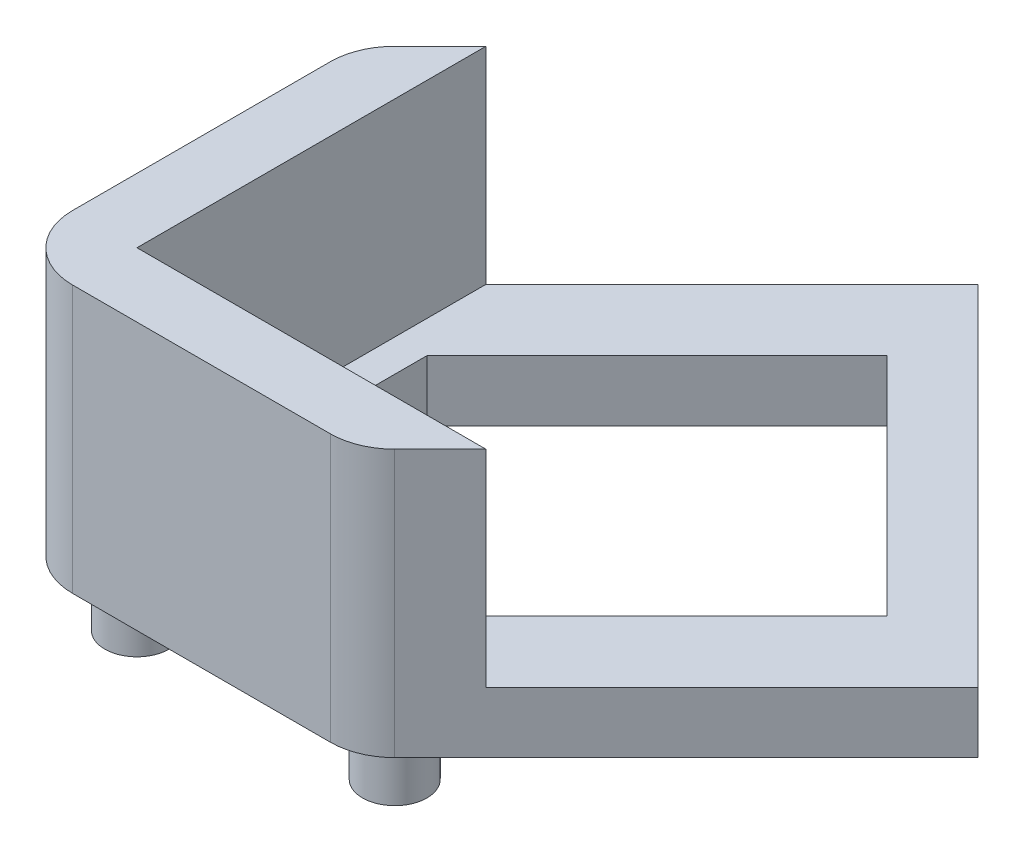
SolidWorks part; units mm, degrees
ref_plane "Front Plane" through (0, 0, 0) normal (0, 0, 1) x (1, 0, 0)
ref_plane "Top Plane" through (0, 0, 0) normal (0, 1, 0) x (1, 0, 0)
ref_plane "Right Plane" through (0, 0, 0) normal (1, 0, 0) x (0, 0, -1)
sketch "Sketch1" plane through (0, 0, 0) normal (0, 1, 0) x (1, 0, 0)
  line L0 (12.7, 0) -> (0, 0)
  line L1 (-1.5875, 0) -> (1.5875, 0)
  line L2 (-1.5875, 0) -> (-1.5875, 12.7)
  line L3 (-1.5875, 12.7) -> (1.5875, 12.7)
  line L4 (1.5875, 0) -> (1.5875, 12.7)
  line L5 (0, 1.5875) -> (12.7, 1.5875)
  line L6 (0, 1.5875) -> (0, -1.5875)
  line L7 (0, -1.5875) -> (12.7, -1.5875)
  line L8 (12.7, 1.5875) -> (12.7, -1.5875)
  line L9 (0, 0) -> (0, 15.875)
  line L10 (0, 15.875) -> (15.875, 0)
  line L11 (15.875, 0) -> (12.7, 0)
  line L12 (-3.175, 12.7) -> (-3.175, 0)
  line L13 (0, -3.175) -> (12.7, -3.175)
  circle A0 centre (0, 0) radius 1.5875
  circle A1 centre (0, 12.7) radius 1.5875
  circle A2 centre (12.7, 0) radius 1.5875
  circle A3 centre (0, 0) radius 3.175
  circle A4 centre (0, 12.7) radius 3.175
  circle A5 centre (12.7, 0) radius 3.175
  dimension "D1" = 3.175
  dimension "D2" = 12.7
  dimension "D3" = 12.7
sketch "Sketch2" plane through (0, 0, 0) normal (0, 1, 0) x (1, 0, 0)
  line L0 (0, -3.175) -> (12.7, -3.175) construction
  line L1 (-3.175, 12.7) -> (-3.175, 0) construction
  line L2 (0, -3.175) -> (12.7, -3.175)
  line L3 (-3.175, 12.7) -> (-3.175, 0)
  line L4 (16.6135, 24.8233) -> (24.8233, 16.6135)
  line L5 (22.5783, 14.3684) -> (14.3684, 22.5783)
  line L6 (-1.5875, 12.7) -> (1.5875, 12.7) construction
  line L12 (1.5875, 9.7974) -> (1.5875, 0)
  line L13 (1.5875, 0) -> (0, 1.5875)
  line L14 (0, 1.5875) -> (9.7974, 1.5875)
  line L15 (16.6135, 24.8233) -> (14.3684, 22.5783)
  line L21 (14.3684, 22.5783) -> (16.6135, 24.8233)
  line L22 (14.3684, 22.5783) -> (12.9171, 24.0296)
  line L23 (1.5875, 12.7) -> (12.9171, 24.0296)
  line L25 (16.6135, 24.8233) -> (12.1233, 29.3135)
  line L27 (12.1233, 29.3135) -> (-2.2451, 14.9451)
  line L28 (1.5875, 9.7974) -> (1.5875, 12.7)
  line L29 (9.7974, 1.5875) -> (12.7, 1.5875)
  line L30 (1.5875, 1.5875) -> (0, 0) construction
  line L31 (12.7, 1.5875) -> (24.0296, 12.9171)
  line L33 (29.3135, 12.1233) -> (14.9451, -2.2451)
  line L34 (24.8233, 16.6135) -> (29.3135, 12.1233)
  line L35 (24.8233, 16.6135) -> (22.5783, 14.3684)
  line L40 (22.5783, 14.3684) -> (24.0296, 12.9171)
  circle A1 centre (0, 0) radius 3.175
  arc A2 (-3.175, 0) -> (0, -3.175) centre (0, 0) ccw
  circle A11 centre (0, 12.7) radius 3.175
  arc A12 (-2.2451, 14.9451) -> (-3.175, 12.7) centre (0, 12.7) ccw
  arc A13 (12.7, -3.175) -> (14.9451, -2.2451) centre (12.7, 0) ccw
  dimension "D2" = 3.175
  dimension "D6" = 6.35
  dimension "D7" = 45
  dimension "D1" = 0
  dimension "D8" = 0
extrude "Boss-Extrude1" add sketch "Sketch2" along normal blind 3
sketch "Sketch5" plane through (0, 0, 0) normal (0, -1, 0) x (1, 0, 0)
  line L0 (0, -1.5875) -> (0, 1.5875) construction
  circle A0 centre (0, 0) radius 1.5875
  circle A1 centre (12.7, 0) radius 1.5875
  circle A2 centre (0, -12.7) radius 1.5875
extrude "Boss-Extrude4" add sketch "Sketch5" along normal blind 3.175
sketch "Sketch6" plane through (0, 3, 0) normal (0, 1, 0) x (1, 0, 0)
  line L0 (1.5875, 1.5875) -> (1.5875, 18.7776)
  line L1 (12.1233, 29.3135) -> (-2.2451, 14.9451) construction
  line L2 (1.5875, 1.5875) -> (18.7776, 1.5875)
  line L3 (29.3135, 12.1233) -> (14.9451, -2.2451) construction
  line L9 (0, -3.175) -> (12.7, -3.175)
  line L10 (14.9451, -2.2451) -> (29.3135, 12.1233)
  line L11 (29.3135, 12.1233) -> (12.1233, 29.3135)
  line L12 (12.1233, 29.3135) -> (-2.2451, 14.9451)
  line L13 (-3.175, 12.7) -> (-3.175, 0)
  line L14 (0, -3.175) -> (12.7, -3.175)
  line L15 (14.9451, -2.2451) -> (29.3135, 12.1233)
  line L16 (29.3135, 12.1233) -> (12.1233, 29.3135)
  line L17 (12.1233, 29.3135) -> (-2.2451, 14.9451)
  line L18 (-3.175, 12.7) -> (-3.175, 0)
  arc A3 (12.7, -3.175) -> (14.9451, -2.2451) centre (12.7, 0) ccw
  arc A4 (-2.2451, 14.9451) -> (-3.175, 12.7) centre (0, 12.7) ccw
  arc A5 (-3.175, 0) -> (0, -3.175) centre (0, 0) ccw
  arc A6 (12.7, -3.175) -> (14.9451, -2.2451) centre (12.7, 0) ccw
  arc A7 (-2.2451, 14.9451) -> (-3.175, 12.7) centre (0, 12.7) ccw
  arc A8 (-3.175, 0) -> (0, -3.175) centre (0, 0) ccw
  line M12 (12.7, 1.5875) -> (1.5875, 1.5875)
  line M13 (1.5875, 1.5875) -> (1.5875, 12.7)
  line M14 (0, -3.175) -> (12.7, -3.175)
  arc M15 (12.7, -3.175) -> (14.9451, -2.2451) centre (12.7, 0) ccw
  line M16 (14.9451, -2.2451) -> (29.3135, 12.1233)
  line M18 (12.1233, 29.3135) -> (-2.2451, 14.9451)
  arc M19 (-2.2451, 14.9451) -> (-3.175, 12.7) centre (0, 12.7) ccw
  line M20 (-3.175, 12.7) -> (-3.175, 0)
  arc M21 (-3.175, 0) -> (0, -3.175) centre (0, 0) ccw
  dimension "D1" = 0
extrude "Boss-Extrude5" add sketch "Sketch6" along normal blind 10.16 contours L2 L0 M12 M13 M18 M19 M20 M21 M14 M15 M16
sketch "Sketch7" plane through (0, 13.16, 0) normal (0, 1, 0) x (1, 0, 0)
  line L0 (0, -3.175) -> (12.7, -3.175) construction
  line L1 (-3.175, 12.7) -> (-3.175, 0) construction
  line L2 (0, -3.175) -> (12.7, -3.175)
  line L3 (-3.175, 12.7) -> (-3.175, 0)
  line L4 (12.7, 1.5875) -> (0, 1.5875)
  line L5 (12.7, -1.5875) -> (12.7, 1.5875)
  line L6 (0, -1.5875) -> (12.7, -1.5875)
  line L7 (0, 1.5875) -> (0, -1.5875)
  line L8 (12.7, 1.5875) -> (1.5875, 1.5875)
  line L9 (12.7, -1.5875) -> (12.7, 0)
  line L10 (0, -1.5875) -> (12.7, -1.5875)
  line L11 (0, 1.5875) -> (0, -1.5875)
  line L12 (-1.5875, 0) -> (1.5875, 0)
  line L13 (1.5875, 0) -> (1.5875, 12.7)
  line L14 (1.5875, 12.7) -> (-1.5875, 12.7)
  line L15 (-1.5875, 12.7) -> (-1.5875, 0)
  line L16 (-1.5875, 0) -> (1.5875, 0)
  line L18 (0, 12.7) -> (-1.5875, 12.7)
  line L19 (-1.5875, 12.7) -> (-1.5875, 0)
  line L20 (15.875, 0) -> (0, 15.875)
  line L21 (12.7, 0) -> (15.875, 0)
  line L22 (0, 0) -> (12.7, 0)
  line L23 (0, 15.875) -> (0, 0)
  line L25 (12.7, 0) -> (15.875, 0)
  line L26 (0, 0) -> (12.7, 0)
  line L27 (0, 15.875) -> (0, 0)
  line L28 (0, 15.875) -> (0, 17.1901)
  line L29 (1.5875, 18.7776) -> (-2.2451, 14.9451) construction
  line L30 (0, 17.1901) -> (1.5875, 18.7776)
  line L31 (1.5875, 18.7776) -> (18.7776, 1.5875)
  line L32 (18.7776, 1.5875) -> (14.9451, -2.2451)
  line L33 (15.875, 0) -> (17.1901, 0)
  circle A1 centre (0, 0) radius 3.175
  arc A2 (0, 3.175) -> (3.175, 0) centre (0, 0) ccw
  circle A3 centre (12.7, 0) radius 1.5875
  arc A4 (11.1125, 0) -> (14.2875, 0) centre (12.7, 0) ccw
  circle A5 centre (0, 12.7) radius 1.5875
  arc A6 (0, 14.2875) -> (0, 11.1125) centre (0, 12.7) ccw
  circle A7 centre (0, 0) radius 1.5875
  arc A8 (0, 1.5875) -> (1.5875, 0) centre (0, 0) ccw
  circle A9 centre (12.7, 0) radius 3.175
  arc A10 (9.525, 0) -> (15.875, 0) centre (12.7, 0) ccw
  circle A11 centre (0, 12.7) radius 3.175
  arc A12 (0, 15.875) -> (0, 9.525) centre (0, 12.7) ccw
  line M19 (18.7776, 1.5875) -> (1.5875, 1.5875)
  line M20 (1.5875, 1.5875) -> (1.5875, 18.7776)
  line M21 (1.5875, 18.7776) -> (-2.2451, 14.9451)
  dimension "D1" = 0
  dimension "D2" = 0
  dimension "D3" = 0
  dimension "D4" = 0
  dimension "D5" = 0
  dimension "D6" = 0
  dimension "D7" = 0
  dimension "D8" = 0
  dimension "D9" = 0
extrude "Cut-Extrude1" cut sketch "Sketch7" against normal up to surface (10.16 mm away) contours L25 L33 L32 L28 L27 L11 L16 L26 M19 M20 M21
